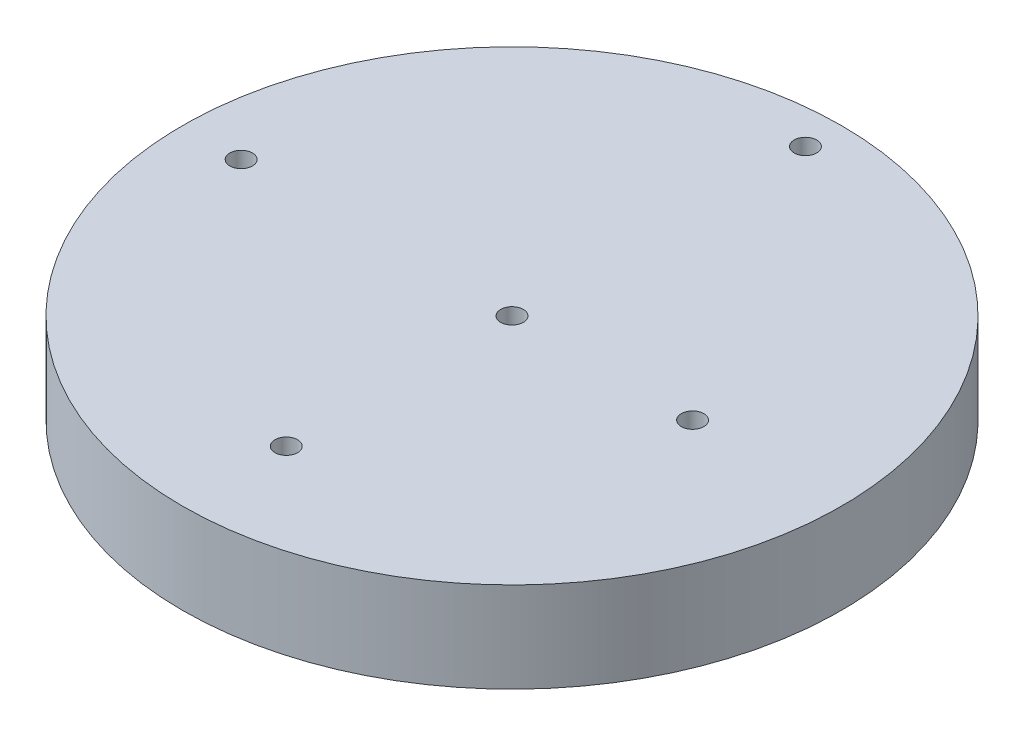
SolidWorks part; units mm, degrees
ref_plane "Front Plane" through (0, 0, 0) normal (0, 0, 1) x (1, 0, 0)
ref_plane "Top Plane" through (0, 0, 0) normal (0, 1, 0) x (1, 0, 0)
ref_plane "Right Plane" through (0, 0, 0) normal (1, 0, 0) x (0, 0, -1)
sketch "Sketch1" plane through (0, 0, 0) normal (0, 1, 0) x (1, 0, 0)
  line L0 (0, -46.355) -> (0, 46.355) construction
  line L1 (-46.355, 0) -> (46.355, 0) construction
  circle A0 centre (0, 0) radius 1.5875
  circle A1 centre (0, 0) radius 46.355
  circle A2 centre (0, 41.275) radius 1.5875
  circle A3 centre (25.4, 0) radius 1.5875
  circle A4 centre (-38.1, 0) radius 1.5875
  circle A5 centre (0, -31.75) radius 1.5875
  point P16 (0, 0)
  dimension "D1" = 3.175
  dimension "D2" = 92.71
  dimension "D3" = 3.175
  dimension "D4" = 3.175
  dimension "D5" = 3.175
  dimension "D6" = 3.175
  dimension "D7" = 41.275
  dimension "D8" = 38.1
  dimension "D9" = 31.75
  dimension "D10" = 25.4
extrude "Boss-Extrude1" add sketch "Sketch1" along normal blind 12.7
